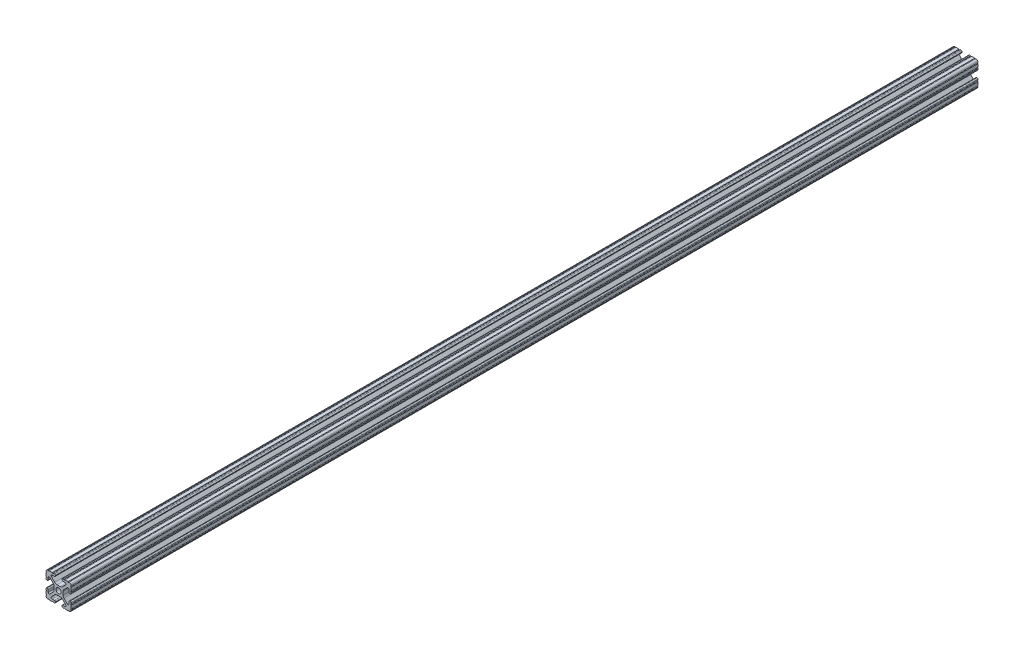
SolidWorks part; units mm, degrees
ref_plane "Front Plane" through (0, 0, 0) normal (0, 0, 1) x (1, 0, 0)
ref_plane "Top Plane" through (0, 0, 0) normal (0, 1, 0) x (1, 0, 0)
ref_plane "Right Plane" through (0, 0, 0) normal (1, 0, 0) x (0, 0, -1)
sketch "Sketch1" plane through (0, 0, 0) normal (0, 0, 1) x (1, 0, 0)
  line L0 (-7.207, 8.7244) -> (-3.8983, 5.4232)
  line L1 (-4.2875, 10.4902) -> (-6.4768, 10.4902)
  line L2 (-3.2385, 11.651) -> (-3.2385, 11.5392)
  line L3 (-5.3171, 12.7) -> (-4.2875, 12.7)
  line L4 (0, 13.4005) -> (0, -14.8534) construction
  line L5 (12.7, 0) -> (-13.9989, 0) construction
  line L6 (-9.5504, 12.7) -> (-6.3331, 12.7)
  line L7 (-12.7, 6.3331) -> (-12.7, 9.5504)
  line L8 (-12.7, 4.2875) -> (-12.7, 5.3171)
  line L9 (-11.5392, 3.2385) -> (-11.651, 3.2385)
  line L10 (-10.4902, 6.4021) -> (-10.4902, 4.2875)
  line L11 (-5.441, 3.8408) -> (-8.7371, 7.1294)
  line L12 (-4.5085, -1.5932) -> (-4.5085, 1.5932)
  line L13 (-1.7093, -4.4958) -> (1.7093, -4.4958)
  line L14 (3.9523, -5.4237) -> (7.1797, -8.6452)
  line L15 (6.4164, -10.4902) -> (4.2875, -10.4902)
  line L16 (3.2385, -11.5392) -> (3.2385, -11.651)
  line L17 (4.2875, -12.7) -> (5.3171, -12.7)
  line L18 (6.3331, -12.7) -> (9.5504, -12.7)
  line L19 (12.7, -9.5504) -> (12.7, -6.3331)
  line L20 (12.7, -5.3171) -> (12.7, -4.2875)
  line L21 (11.651, -3.2385) -> (11.5392, -3.2385)
  line L22 (10.4902, -4.2875) -> (10.4902, -6.4021)
  line L23 (8.7371, -7.1294) -> (5.441, -3.8408)
  line L24 (4.5085, -1.5932) -> (4.5085, 1.5932)
  line L25 (5.441, 3.8408) -> (8.7371, 7.1294)
  line L26 (10.4902, 6.4021) -> (10.4902, 4.2875)
  line L27 (11.5392, 3.2385) -> (11.651, 3.2385)
  line L28 (12.7, 4.2875) -> (12.7, 5.3171)
  line L29 (12.7, 6.3331) -> (12.7, 9.5504)
  line L30 (9.5504, 12.7) -> (6.3331, 12.7)
  line L31 (5.3171, 12.7) -> (4.2875, 12.7)
  line L32 (3.2385, 11.651) -> (3.2385, 11.5392)
  line L33 (4.2875, 10.4902) -> (6.4768, 10.4902)
  line L34 (7.207, 8.7244) -> (3.8983, 5.4232)
  line L35 (1.6558, 4.4958) -> (-1.6558, 4.4958)
  line L36 (-8.7371, -7.1294) -> (-5.441, -3.8408)
  line L37 (-10.4902, -4.2875) -> (-10.4902, -6.4021)
  line L38 (-11.651, -3.2385) -> (-11.5392, -3.2385)
  line L39 (-12.7, -5.3171) -> (-12.7, -4.2875)
  line L40 (-12.7, -9.5504) -> (-12.7, -6.3331)
  line L41 (-6.3331, -12.7) -> (-9.5504, -12.7)
  line L42 (-4.2875, -12.7) -> (-5.3171, -12.7)
  line L43 (-3.2385, -11.5392) -> (-3.2385, -11.651)
  line L44 (-6.4164, -10.4902) -> (-4.2875, -10.4902)
  line L45 (-3.9523, -5.4237) -> (-7.1797, -8.6452)
  arc A0 (-7.207, 8.7244) -> (-6.4768, 10.4902) centre (-6.4768, 9.4563) cw
  arc A1 (-3.2385, 11.5392) -> (-4.2875, 10.4902) centre (-4.2875, 11.5392) cw
  arc A2 (-4.2875, 12.7) -> (-3.2385, 11.651) centre (-4.2875, 11.651) cw
  arc A3 (-5.3171, 12.7) -> (-6.3331, 12.7) centre (-5.8251, 12.7) cw
  arc A4 (-9.5504, 12.7) -> (-10.5664, 12.6998) centre (-10.0584, 12.7) cw
  arc A5 (-12.6998, 10.5664) -> (-10.5664, 12.6998) centre (-10.5918, 10.5918) cw
  arc A6 (-12.6998, 10.5664) -> (-12.7, 9.5504) centre (-12.7, 10.0584) cw
  arc A7 (-12.7, 6.3331) -> (-12.7, 5.3171) centre (-12.7, 5.8251) cw
  arc A8 (-11.651, 3.2385) -> (-12.7, 4.2875) centre (-11.651, 4.2875) cw
  arc A9 (-10.4902, 4.2875) -> (-11.5392, 3.2385) centre (-11.5392, 4.2875) cw
  circle A10 centre (0, 0) radius 2.6035
  arc A11 (-10.4902, 6.4021) -> (-8.7371, 7.1294) centre (-9.4628, 6.4021) cw
  arc A12 (-5.441, 3.8408) -> (-4.5085, 1.5932) centre (-7.6835, 1.5932) cw
  arc A13 (-4.5085, -1.5932) -> (-5.441, -3.8408) centre (-7.6835, -1.5932) cw
  arc A14 (-8.7371, -7.1294) -> (-10.4902, -6.4021) centre (-9.4628, -6.4021) cw
  arc A15 (-1.7093, -4.4958) -> (-3.9523, -5.4237) centre (-1.7093, -7.6708) ccw
  arc A16 (3.9523, -5.4237) -> (1.7093, -4.4958) centre (1.7093, -7.6708) ccw
  arc A17 (6.4164, -10.4902) -> (7.1797, -8.6452) centre (6.4164, -9.4098) ccw
  arc A18 (4.2875, -10.4902) -> (3.2385, -11.5392) centre (4.2875, -11.5392) ccw
  arc A19 (3.2385, -11.651) -> (4.2875, -12.7) centre (4.2875, -11.651) ccw
  arc A20 (6.3331, -12.7) -> (5.3171, -12.7) centre (5.8251, -12.7) ccw
  arc A21 (10.5664, -12.6998) -> (9.5504, -12.7) centre (10.0584, -12.7) ccw
  arc A22 (10.5664, -12.6998) -> (12.6998, -10.5664) centre (10.5918, -10.5918) ccw
  arc A23 (12.7, -9.5504) -> (12.6998, -10.5664) centre (12.7, -10.0584) ccw
  arc A24 (12.7, -5.3171) -> (12.7, -6.3331) centre (12.7, -5.8251) ccw
  arc A25 (12.7, -4.2875) -> (11.651, -3.2385) centre (11.651, -4.2875) ccw
  arc A26 (11.5392, -3.2385) -> (10.4902, -4.2875) centre (11.5392, -4.2875) ccw
  arc A27 (8.7371, -7.1294) -> (10.4902, -6.4021) centre (9.4628, -6.4021) ccw
  arc A28 (4.5085, -1.5932) -> (5.441, -3.8408) centre (7.6835, -1.5932) ccw
  arc A29 (5.441, 3.8408) -> (4.5085, 1.5932) centre (7.6835, 1.5932) ccw
  arc A30 (10.4902, 6.4021) -> (8.7371, 7.1294) centre (9.4628, 6.4021) ccw
  arc A31 (10.4902, 4.2875) -> (11.5392, 3.2385) centre (11.5392, 4.2875) ccw
  arc A32 (11.651, 3.2385) -> (12.7, 4.2875) centre (11.651, 4.2875) ccw
  arc A33 (12.7, 6.3331) -> (12.7, 5.3171) centre (12.7, 5.8251) ccw
  arc A34 (12.6998, 10.5664) -> (12.7, 9.5504) centre (12.7, 10.0584) ccw
  arc A35 (12.6998, 10.5664) -> (10.5664, 12.6998) centre (10.5918, 10.5918) ccw
  arc A36 (9.5504, 12.7) -> (10.5664, 12.6998) centre (10.0584, 12.7) ccw
  arc A37 (5.3171, 12.7) -> (6.3331, 12.7) centre (5.8251, 12.7) ccw
  arc A38 (4.2875, 12.7) -> (3.2385, 11.651) centre (4.2875, 11.651) ccw
  arc A39 (3.2385, 11.5392) -> (4.2875, 10.4902) centre (4.2875, 11.5392) ccw
  arc A40 (7.207, 8.7244) -> (6.4768, 10.4902) centre (6.4768, 9.4563) ccw
  arc A41 (1.6558, 4.4958) -> (3.8983, 5.4232) centre (1.6558, 7.6708) ccw
  arc A42 (-1.6558, 4.4958) -> (-3.8983, 5.4232) centre (-1.6558, 7.6708) cw
  arc A43 (-11.5392, -3.2385) -> (-10.4902, -4.2875) centre (-11.5392, -4.2875) cw
  arc A44 (-12.7, -4.2875) -> (-11.651, -3.2385) centre (-11.651, -4.2875) cw
  arc A45 (-12.7, -5.3171) -> (-12.7, -6.3331) centre (-12.7, -5.8251) cw
  arc A46 (-12.7, -9.5504) -> (-12.6998, -10.5664) centre (-12.7, -10.0584) cw
  arc A47 (-10.5664, -12.6998) -> (-12.6998, -10.5664) centre (-10.5918, -10.5918) cw
  arc A48 (-10.5664, -12.6998) -> (-9.5504, -12.7) centre (-10.0584, -12.7) cw
  arc A49 (-6.3331, -12.7) -> (-5.3171, -12.7) centre (-5.8251, -12.7) cw
  arc A50 (-3.2385, -11.651) -> (-4.2875, -12.7) centre (-4.2875, -11.651) cw
  arc A51 (-4.2875, -10.4902) -> (-3.2385, -11.5392) centre (-4.2875, -11.5392) cw
  arc A52 (-6.4164, -10.4902) -> (-7.1797, -8.6452) centre (-6.4164, -9.4098) cw
  dimension "D1" = 5.207
  dimension "D9" = 14.859
  dimension "D2" = 25.4
  dimension "D3" = 12.7
  dimension "D4" = 6.477
  dimension "D5" = 8.2042
  dimension "D6" = 9.017
  dimension "D8" = 2.2098
  dimension "D10" = 2.2098
extrude "Extrude1" add sketch "Sketch1" against normal blind 914.4
